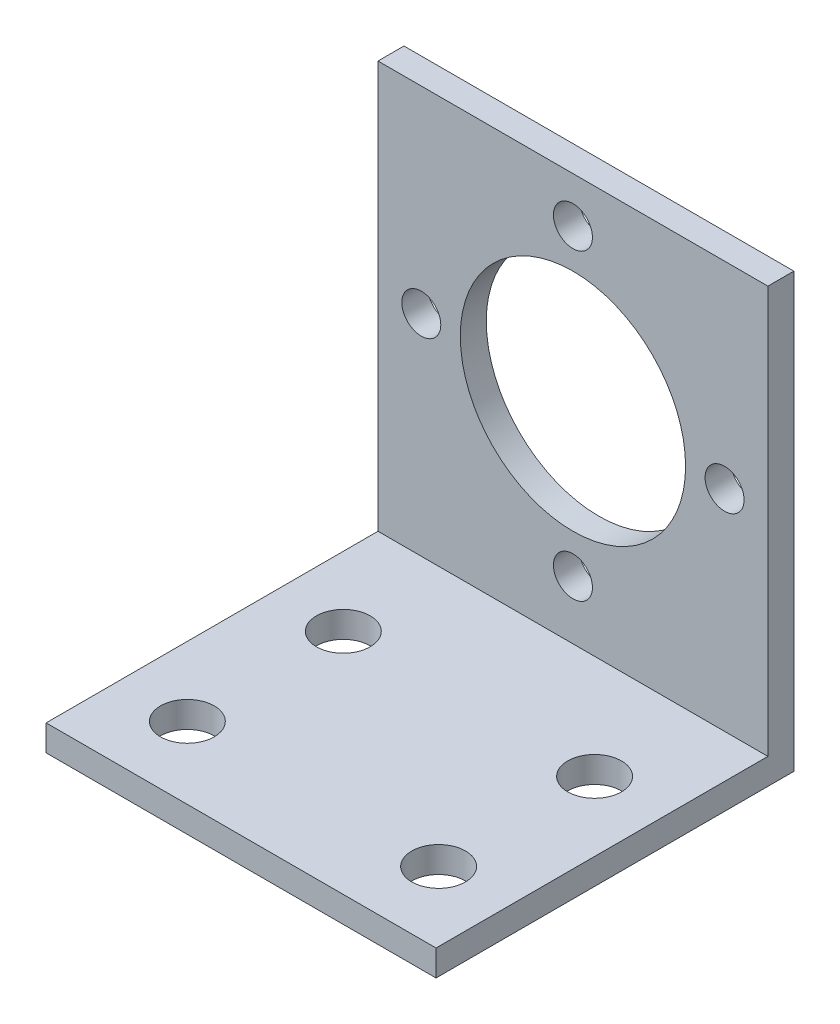
SolidWorks part; units mm, degrees
ref_plane "前视基准面" through (0, 0, 0) normal (0, 0, 1) x (1, 0, 0)
ref_plane "上视基准面" through (0, 0, 0) normal (0, 1, 0) x (1, 0, 0)
ref_plane "右视基准面" through (0, 0, 0) normal (1, 0, 0) x (0, 0, -1)
other "Configuration Table"
sketch "草图1" plane through (0, 0, 0) normal (0, 0, 1) x (1, 0, 0)
  line L1 (0, 0) -> (45, 0)
  line L2 (0, 0) -> (0, 50)
  line L3 (0, 50) -> (45, 50)
  line L4 (45, 0) -> (45, 50)
  dimension "D1" = 50
  dimension "D2" = 45
extrude "凸台-拉伸1" add sketch "草图1" along normal blind 3
sketch "草图2" plane through (0, 0, 0) normal (0, 0, -1) x (-1, 0, 0)
  line L0 (-45, 0) -> (-45, 3)
  line L1 (-45, 0) -> (-45, 50) construction
  line L2 (-45, 3) -> (0, 3)
  line L3 (0, 50) -> (0, 0) construction
  line L4 (0, 3) -> (0, 0)
  line L5 (0, 0) -> (-45, 0)
  dimension "D1" = 3
extrude "凸台-拉伸2" add sketch "草图2" against normal blind 41.3
sketch "草图3" plane through (0, 0, 3) normal (0, 0, 1) x (1, 0, 0)
  line L0 (45, 3) -> (45, 50) construction
  line L2 (22.5, 50) -> (22.5, 47) construction
  line L4 (45, 50) -> (0, 50) construction
  line L5 (22.5, 42.5) -> (22.5, 40.25) construction
  circle A0 centre (22.5, 27.25) radius 17.5 construction
  circle A1 centre (22.5, 27.25) radius 13
  circle A2 centre (22.5, 44.75) radius 2.25
  circle A3 centre (40, 27.25) radius 2.25
  circle A4 centre (22.5, 9.75) radius 2.25
  circle A5 centre (5, 27.25) radius 2.25
  point P19 (22.5, 47)
  dimension "D1" = 35
  dimension "D2" = 26
  dimension "D3" = 4.5
  dimension "D4" = 22.5
  dimension "D5" = 3
extrude "切除-拉伸1" cut sketch "草图3" against normal through all
sketch "草图4" plane through (0, 3, 0) normal (0, 1, 0) x (1, 0, 0)
  line L0 (45, -41.3) -> (45, -3) construction
  line L1 (8, -15) -> (37, -15) construction
  line L2 (8, -15) -> (8, -33) construction
  line L3 (8, -33) -> (37, -33) construction
  line L4 (37, -15) -> (37, -33) construction
  line L5 (0, -41.3) -> (45, -41.3) construction
  circle A0 centre (37, -15) radius 3.1
  circle A1 centre (37, -33) radius 3.1
  circle A2 centre (8, -33) radius 3.1
  circle A3 centre (8, -15) radius 3.1
  dimension "D5" = 6.2
  dimension "D1" = 29
  dimension "D2" = 8
  dimension "D3" = 18
  dimension "D4" = 8.3
extrude "切除-拉伸2" cut sketch "草图4" against normal through all
